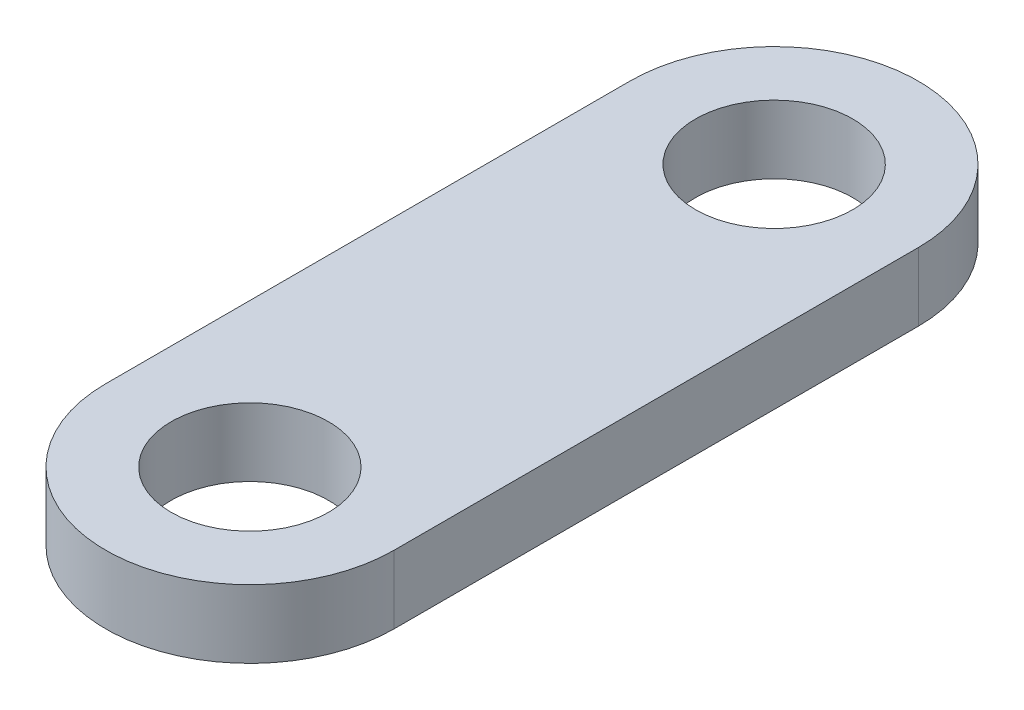
SolidWorks part; units mm, degrees
ref_plane "前视基准面" through (0, 0, 0) normal (0, 0, 1) x (1, 0, 0)
ref_plane "上视基准面" through (0, 0, 0) normal (0, 1, 0) x (1, 0, 0)
ref_plane "右视基准面" through (0, 0, 0) normal (1, 0, 0) x (0, 0, -1)
other "Configuration Table"
sketch "草图1" plane through (0, 0, 0) normal (0, 1, 0) x (1, 0, 0)
  line L0 (0, -10) -> (0, 10) construction
  line L1 (-5.5, -10) -> (-5.5, 10)
  line L2 (5.5, -10) -> (5.5, 10)
  arc A0 (-5.5, -10) -> (5.5, -10) centre (0, -10) ccw
  arc A1 (5.5, 10) -> (-5.5, 10) centre (0, 10) ccw
  circle A2 centre (0, 10) radius 3
  circle A3 centre (0, -10) radius 3
  point P3 (0, 0)
  dimension "D2" = 5.5
  dimension "D3" = 6
  dimension "D1" = 20
extrude "凸台-拉伸1" add sketch "草图1" along normal blind 2.6
